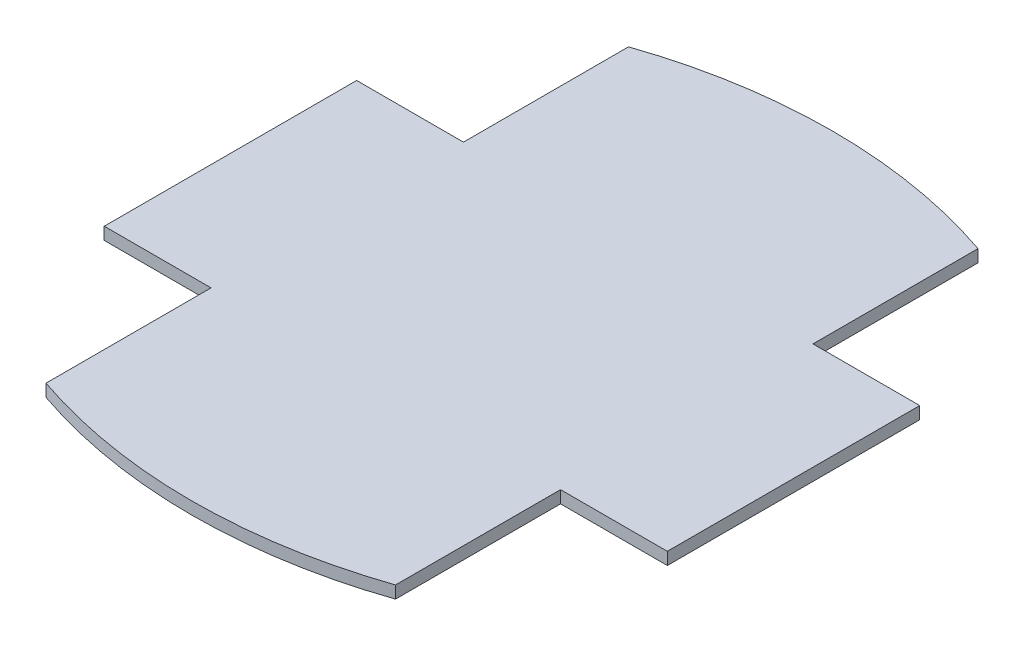
SolidWorks part; units mm, degrees
ref_plane "Plan de face" through (0, 0, 0) normal (0, 0, 1) x (1, 0, 0)
ref_plane "Plan de dessus" through (0, 0, 0) normal (0, 1, 0) x (1, 0, 0)
ref_plane "Plan de droite" through (0, 0, 0) normal (1, 0, 0) x (0, 0, -1)
sketch "Esquisse1" plane through (0, 0, 0) normal (0, 1, 0) x (1, 0, 0)
  line L0 (-145, 0) -> (0, 0) construction
  line L1 (-90, -150) -> (90, -150)
  line L2 (-90, -150) -> (-90, 150)
  line L3 (-90, 150) -> (90, 150)
  line L4 (90, -150) -> (90, 150)
  line L5 (-90, -150) -> (90, 150) construction
  line L6 (-90, 150) -> (90, -150) construction
  line L7 (-90, 65) -> (-145, 65)
  line L8 (-90, 65) -> (-90, -65)
  line L9 (-90, -65) -> (-145, -65)
  line L10 (-145, 65) -> (-145, -65)
  line L11 (0, 0) -> (0, -275) construction
  line L12 (90, -65) -> (145, -65)
  line L13 (145, 65) -> (145, -65)
  line L14 (90, 65) -> (145, 65)
  line L15 (90, 65) -> (90, -65)
  arc A0 (-90, 150) -> (90, 150) centre (0, -112.5) cw
  arc A1 (-90, -150) -> (90, -150) centre (0, 112.5) ccw
  point P0 (0, 0)
  point P18 (0, -159.5923)
  point P19 (0, 165)
  point P20 (0, -165)
  dimension "D1" = 180
  dimension "D2" = 300
  dimension "D3" = 85
  dimension "D4" = 55
  dimension "D5" = 15
  dimension "D6" = 15
extrude "Boss.-Extru.1" add sketch "Esquisse1" along normal blind 6.35 contours L1 L4 L3 L2 | L7 L10 L9 L2 | L14 L4 L12 L13 | L1 A1 | A0 L3
ref_plane "Plan1" through (0, 0, 150) normal (0, 0, -1) x (-1, 0, 0)
ref_plane "Plan3" through (0, 0, -150) normal (0, 0, -1) x (-1, 0, 0)
ref_plane "Wheel axis1" through (0, 0, 107.5) normal (0, 0, 1) x (1, 0, 0)
ref_plane "Wheel axis2" through (0, 0, -107.5) normal (0, 0, -1) x (-1, 0, 0)
